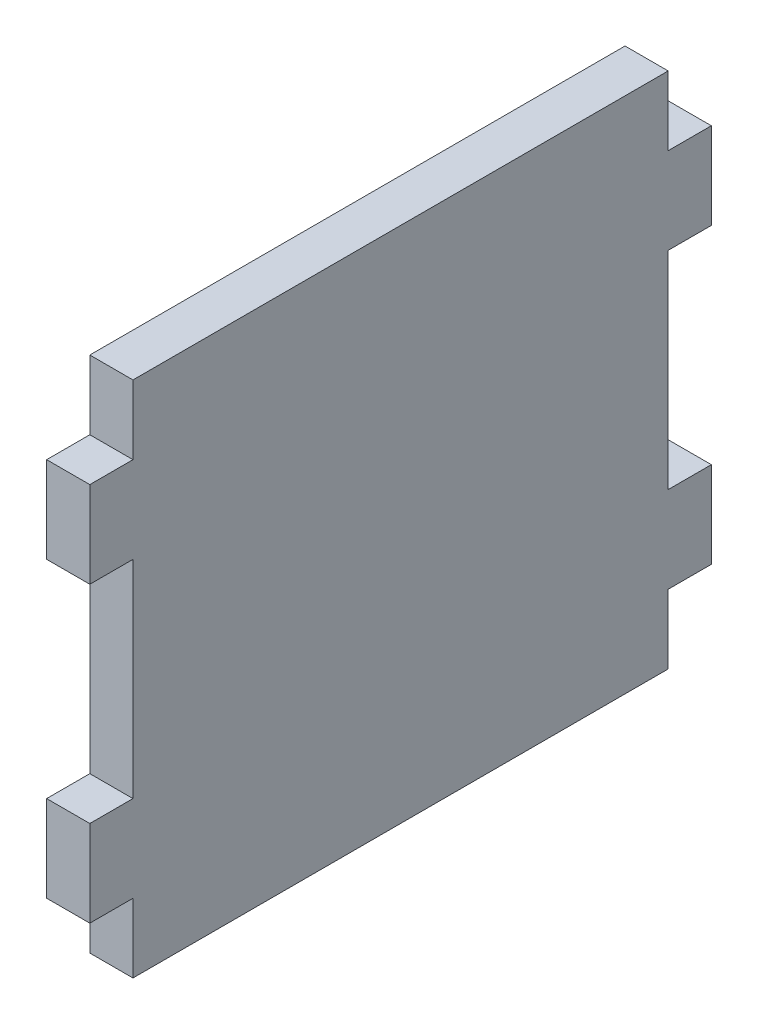
SolidWorks part; units mm, degrees
ref_plane "Front Plane" through (0, 0, 0) normal (1, 0, 0) x (0, 1, 0)
ref_plane "Top Plane" through (0, 0, 0) normal (0, 0, 1) x (0, 1, 0)
ref_plane "Right Plane" through (0, 0, 0) normal (0, 1, 0) x (-1, 0, 0)
sketch "Sketch1" plane through (0, 0, 0) normal (1, 0, 0) x (0, 1, 0)
  line L0 (0, 28) -> (-12, 28) construction
  line L2 (-30, -28) -> (-30, 28)
  line L3 (-30, 28) -> (-22, 28)
  line L4 (30, -28) -> (30, 28)
  line L5 (-30, -28) -> (30, 28) construction
  line L6 (-30, 28) -> (30, -28) construction
  line L7 (-12, 28) -> (-12, 33)
  line L8 (-12, 33) -> (-22, 33)
  line L9 (-22, 33) -> (-22, 28)
  line L10 (0, 28) -> (0, 0) construction
  line L11 (-12, 28) -> (12, 28)
  line L12 (12, 28) -> (12, 33)
  line L13 (12, 33) -> (22, 33)
  line L14 (22, 33) -> (22, 28)
  line L15 (22, 28) -> (30, 28)
  line L16 (0, 0) -> (-30, 0) construction
  line L25 (-30, -28) -> (-30, -34)
  line L26 (-30, -34) -> (-22, -34)
  line L27 (-22, -34) -> (-22, -39)
  line L28 (-22, -39) -> (-12, -39)
  line L29 (-12, -39) -> (-12, -34)
  line L30 (-12, -34) -> (12, -34)
  line L31 (12, -34) -> (12, -39)
  line L32 (12, -39) -> (22, -39)
  line L33 (22, -39) -> (22, -34)
  line L34 (22, -34) -> (30, -34)
  line L35 (30, -34) -> (30, -28)
  point P0 (0, 0)
  dimension "D1" = 60
  dimension "D2" = 6
  dimension "D3" = 12
  dimension "D4" = 10
  dimension "D5" = 5
  dimension "D6" = 10
  dimension "D7" = 24
  dimension "D8" = 5
extrude "Boss-Extrude1" add sketch "Sketch1" along normal blind 5
sketch "Sketch2" plane through (0, 0, 0) normal (1, 0, 0) x (0, 1, 0)
  line L0 (0, 28) -> (0, -34) construction
  line L1 (12, 28) -> (-12, 28) construction
  line L2 (-12, -34) -> (12, -34) construction
  line L3 (0, -3) -> (20, -3) construction
  dimension "D1" = 20
